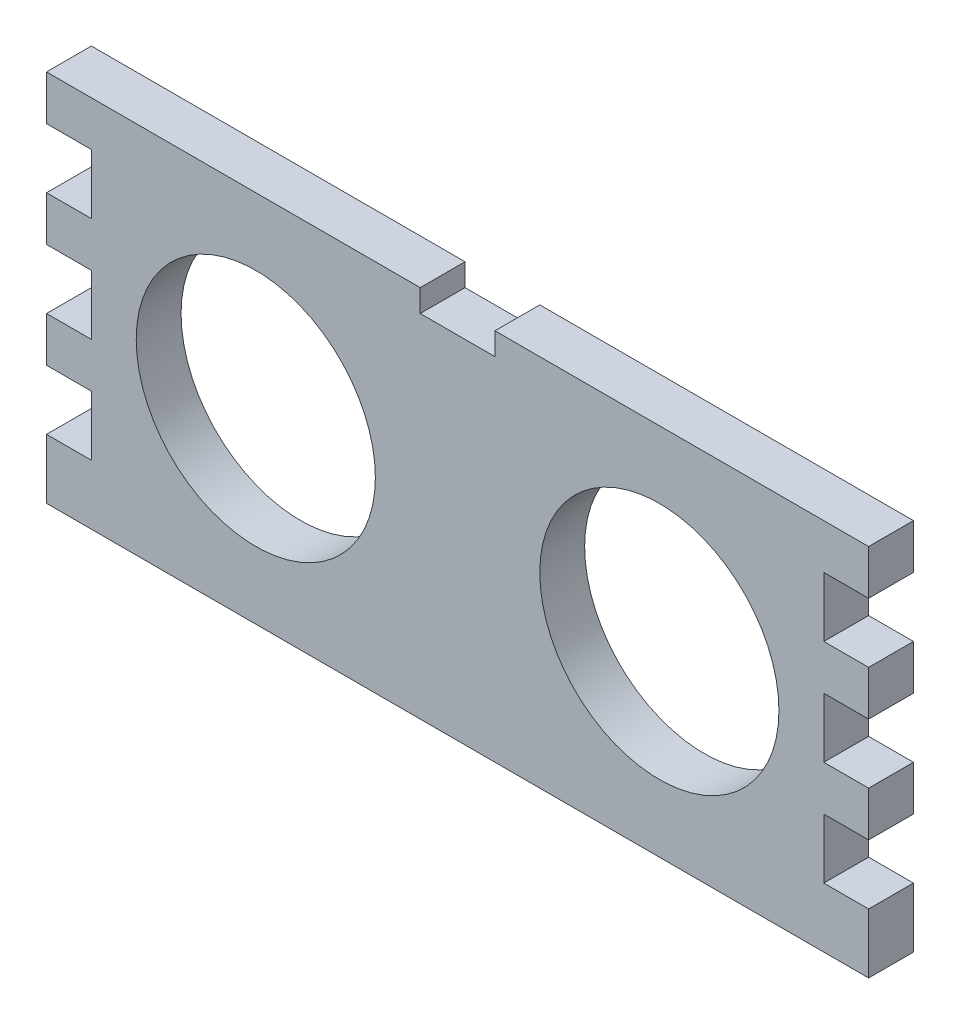
SolidWorks part; units mm, degrees
ref_plane "Plan de face" through (0, 0, 0) normal (0, 0, 1) x (1, 0, 0)
ref_plane "Plan de dessus" through (0, 0, 0) normal (0, 1, 0) x (1, 0, 0)
ref_plane "Plan de droite" through (0, 0, 0) normal (1, 0, 0) x (0, 0, -1)
sketch "Sketch1" plane through (0, 0, 0) normal (0, 0, 1) x (1, 0, 0)
  line L1 (-27.5, -12.5) -> (27.5, -12.5)
  line L2 (-27.5, -12.5) -> (-27.5, 12.5)
  line L3 (-27.5, 12.5) -> (27.5, 12.5)
  line L4 (27.5, -12.5) -> (27.5, 12.5)
  line L5 (-27.5, -12.5) -> (27.5, 12.5) construction
  line L6 (-27.5, 12.5) -> (27.5, -12.5) construction
  point P0 (0, 0)
  dimension "D1" = 55
  dimension "D2" = 25
extrude "Boss-Extrude1" add sketch "Sketch1" along normal blind 3
sketch "Sketch2" plane through (0, 0, 3) normal (0, 0, 1) x (1, 0, 0)
  line L0 (27.5, -12.5) -> (27.5, 12.5) construction
  line L2 (27.5, 12.5) -> (-27.5, 12.5) construction
  circle A0 centre (-13.5, 0) radius 8
  circle A1 centre (13.5, 0) radius 8
  dimension "D1" = 16
  dimension "D2" = 16
  dimension "D4" = 14
  dimension "D5" = 12.5
  dimension "D3" = 27
  dimension "D6" = 12.5
extrude "Cut-Extrude1" cut sketch "Sketch2" against normal blind 3
sketch "Sketch3" plane through (0, 0, 3) normal (0, 0, 1) x (1, 0, 0)
  line L0 (-27.5, 12.5) -> (-27.5, -12.5) construction
  line L1 (-27.5, 9.5) -> (-24.5, 9.5)
  line L2 (-27.5, 9.5) -> (-27.5, 5.5)
  line L3 (-27.5, 5.5) -> (-24.5, 5.5)
  line L4 (-24.5, 9.5) -> (-24.5, 5.5)
  line L5 (27.5, 12.5) -> (-27.5, 12.5) construction
  line L6 (-27.5, -12.5) -> (27.5, -12.5) construction
  line L7 (-27.5, 2.5) -> (-24.5, 2.5)
  line L8 (-27.5, 2.5) -> (-27.5, -1.5)
  line L9 (-27.5, -1.5) -> (-24.5, -1.5)
  line L10 (-24.5, 2.5) -> (-24.5, -1.5)
  line L11 (-27.5, -4.5) -> (-24.5, -4.5)
  line L12 (-27.5, -4.5) -> (-27.5, -8.5)
  line L13 (-27.5, -8.5) -> (-24.5, -8.5)
  line L14 (-24.5, -4.5) -> (-24.5, -8.5)
  dimension "D1" = 3
  dimension "D2" = 4
  dimension "D3" = 3
  dimension "D4" = 4
  dimension "D5" = 3
  dimension "D6" = 3
  dimension "D7" = 3
  dimension "D8" = 4
  dimension "D9" = 3
  dimension "D10" = 4
extrude "Cut-Extrude2" cut sketch "Sketch3" against normal blind 3
sketch "Sketch4" plane through (0, 0, 3) normal (0, 0, 1) x (1, 0, 0)
  line L0 (27.5, -12.5) -> (27.5, 12.5) construction
  line L1 (27.5, 9.5) -> (24.5, 9.5)
  line L2 (27.5, 9.5) -> (27.5, 5.5)
  line L3 (27.5, 5.5) -> (24.5, 5.5)
  line L4 (24.5, 9.5) -> (24.5, 5.5)
  line L5 (27.5, 12.5) -> (-27.5, 12.5) construction
  line L6 (-27.5, -12.5) -> (27.5, -12.5) construction
  line L7 (27.5, 2.5) -> (24.5, 2.5)
  line L8 (27.5, 2.5) -> (27.5, -1.5)
  line L9 (27.5, -1.5) -> (24.5, -1.5)
  line L10 (24.5, 2.5) -> (24.5, -1.5)
  line L11 (27.5, -4.5) -> (24.5, -4.5)
  line L12 (27.5, -4.5) -> (27.5, -8.5)
  line L13 (27.5, -8.5) -> (24.5, -8.5)
  line L14 (24.5, -4.5) -> (24.5, -8.5)
  dimension "D1" = 3
  dimension "D2" = 4
  dimension "D3" = 3
  dimension "D4" = 4
  dimension "D5" = 3
  dimension "D6" = 3
  dimension "D7" = 4
  dimension "D8" = 3
  dimension "D9" = 3
  dimension "D10" = 4
extrude "Cut-Extrude3" cut sketch "Sketch4" against normal blind 3
sketch "Sketch5" plane through (0, 0, 3) normal (0, 0, 1) x (1, 0, 0)
  line L0 (27.5, 12.5) -> (-27.5, 12.5) construction
  line L1 (-2.5, 12.5) -> (2.5, 12.5)
  line L2 (-2.5, 12.5) -> (-2.5, 11)
  line L3 (-2.5, 11) -> (2.5, 11)
  line L4 (2.5, 12.5) -> (2.5, 11)
  line L5 (-27.5, 12.5) -> (-27.5, 9.5) construction
  dimension "D1" = 5
  dimension "D2" = 1.5
  dimension "D3" = 25
extrude "Cut-Extrude4" cut sketch "Sketch5" against normal blind 10
